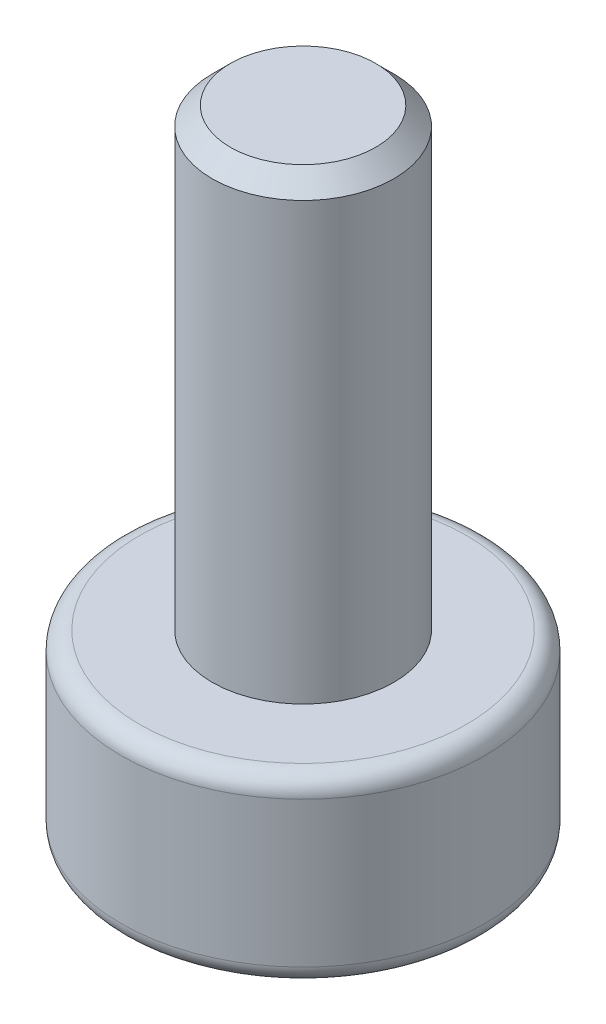
SolidWorks part; units mm, degrees
material "AISI 304"
ref_plane "前视基准面" through (0, 0, 0) normal (0, 0, 1) x (1, 0, 0)
ref_plane "上视基准面" through (0, 0, 0) normal (0, 1, 0) x (1, 0, 0)
ref_plane "右视基准面" through (0, 0, 0) normal (1, 0, 0) x (0, 0, -1)
sketch "草图2" plane through (0, 0, 0) normal (0, 1, 0) x (1, 0, 0)
  circle A0 centre (0, 0) radius 2
  dimension "D1" = 4
extrude "凸台-拉伸1" add sketch "草图2" along normal blind 2
sketch "草图3" plane through (0, 2, 0) normal (0, 1, 0) x (1, 0, 0)
  circle A0 centre (0, 0) radius 1
  dimension "D1" = 2
extrude "凸台-拉伸2" add sketch "草图3" along normal blind 5
fillet "圆角1" radius 0.2 2 edges at (0, 2, 2) (0, 0, 2)
sketch "草图4" plane through (0, 0, 0) normal (0, -1, 0) x (1, 0, 0)
  circle A0 centre (0, 0) radius 0.765
  dimension "D1" = 1.53
extrude "切除-拉伸1" cut sketch "草图4" against normal blind 1.52
chamfer "倒角1" distance 0.1 angle 45 1 edges at (0, 0, -0.765)
chamfer "倒角2" distance 0.2 angle 45 1 edges at (0, 7, 1)
